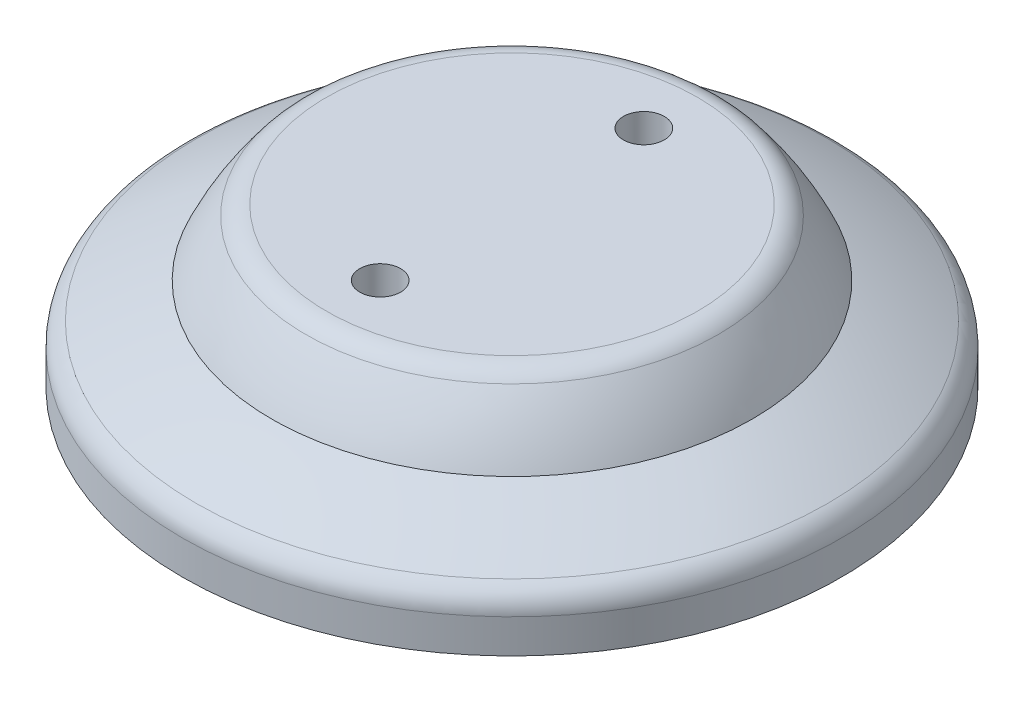
SolidWorks part; units mm, degrees
ref_plane "Alzado" through (0, 0, 0) normal (0, 0, 1) x (1, 0, 0)
ref_plane "Planta" through (0, 0, 0) normal (0, 1, 0) x (1, 0, 0)
ref_plane "Vista lateral" through (0, 0, 0) normal (1, 0, 0) x (0, 0, -1)
sketch "Croquis3" plane through (0, 0, 0) normal (0, 0, 1) x (1, 0, 0)
  line L0 (0, 0) -> (0, 12) construction
  line L1 (0, 12) -> (15, 12)
  line L2 (0, 0) -> (0, 12)
  line L3 (18.2288, 7) -> (0, 7) construction
  line L4 (0, 0) -> (25, 0)
  line L5 (25, 0) -> (25, 3.7426)
  arc A0 (18.2288, 7) -> (15, 12) centre (0, -1.2288) ccw
  arc A1 (25, 3.7426) -> (18.2288, 7) centre (0, -39.5587) ccw
  dimension "D3" = 40
  dimension "D4" = 100
  dimension "D1" = 12
  dimension "D2" = 15
  dimension "D6" = 5
  dimension "D7" = 25
revolve "Revolución1" add sketch "Croquis3" angle 360 about L2
sketch "Croquis4" plane through (0, 0, 0) normal (0, 0, 1) x (1, 0, 0)
  line L0 (0, 1.5) -> (0, 10.5)
  line L2 (0, 10.5) -> (0, 12) construction
  line L3 (15, 12) -> (-15, 12) construction
  line L8 (14.3069, 10.5) -> (-14.3069, 10.5)
  line L9 (-23.5, 1.5) -> (23.5, 1.5)
  line L10 (14.3069, 10.5) -> (0, 10.5)
  line L11 (0, 1.5) -> (23.5, 1.5)
  line L12 (-23.5, 2.8677) -> (-23.5, 1.5)
  line L14 (23.5, 1.5) -> (23.5, 2.8677)
  line L15 (23.5, 1.5) -> (23.5, 2.8677)
  arc A8 (-17.1021, 5.826) -> (-23.5, 2.8677) centre (0, -39.5587) ccw
  arc A9 (-14.3069, 10.5) -> (-17.1021, 5.826) centre (0, -1.2288) ccw
  arc A10 (23.5, 2.8677) -> (17.1021, 5.826) centre (0, -39.5587) ccw
  arc A11 (17.1021, 5.826) -> (14.3069, 10.5) centre (0, -1.2288) ccw
  arc A14 (23.5, 2.8677) -> (17.1021, 5.826) centre (0, -39.5587) ccw
  arc A15 (17.1021, 5.826) -> (14.3069, 10.5) centre (0, -1.2288) ccw
  dimension "D1" = 1.5
revolve "Cortar-Revolución1" cut sketch "Croquis4" angle 360 about L2
sketch "Croquis6" plane through (0, 0, 0) normal (0, -1, 0) x (1, 0, 0)
  circle A1 centre (0, 0) radius 23.5 construction
  circle A2 centre (0, 0) radius 23.5
extrude "Cortar-Extruir2" cut sketch "Croquis6" against normal blind 0.5
sketch "Croquis7" plane through (0, 10.5, 0) normal (0, -1, 0) x (1, 0, 0)
  line L0 (0, 0) -> (0, 14.3069) construction
  line L1 (-14.3069, 0) -> (14.3069, 0) construction
  circle A0 centre (0, 0) radius 14.3069 construction
  circle A1 centre (0, 10) radius 1.55
  circle A2 centre (0, 10) radius 3.05
  circle A3 centre (0, -10) radius 1.55
  circle A4 centre (0, -10) radius 3.05
  dimension "D1" = 3.1
  dimension "D3" = 1.5
  dimension "D2" = 10
extrude "Saliente-Extruir1" add sketch "Croquis7" along normal offset from surface (9.5 mm away) 1 up to face at (0, 0, -23.5)
sketch "Croquis8" plane through (0, 10.5, 0) normal (0, -1, 0) x (1, 0, 0)
  circle A0 centre (0, -10) radius 1.55 construction
  circle A1 centre (0, 10) radius 1.55 construction
  circle A2 centre (0, -10) radius 1.55
  circle A3 centre (0, 10) radius 1.55
extrude "Cortar-Extruir3" cut sketch "Croquis8" against normal blind 5.5
fillet "Redondeo1" radius 2 1 edges at (0, 12, -15)
fillet "Redondeo2" radius 2 1 edges at (0, 3.7426, -25)
sketch "Croquis9" plane through (0, 0.5, 0) normal (0, -1, 0) x (1, 0, 0)
  circle A0 centre (0, 0) radius 23.5 construction
  circle A1 centre (0, 0) radius 23.5
extrude "Cortar-Extruir4" cut sketch "Croquis9" against normal blind 1
